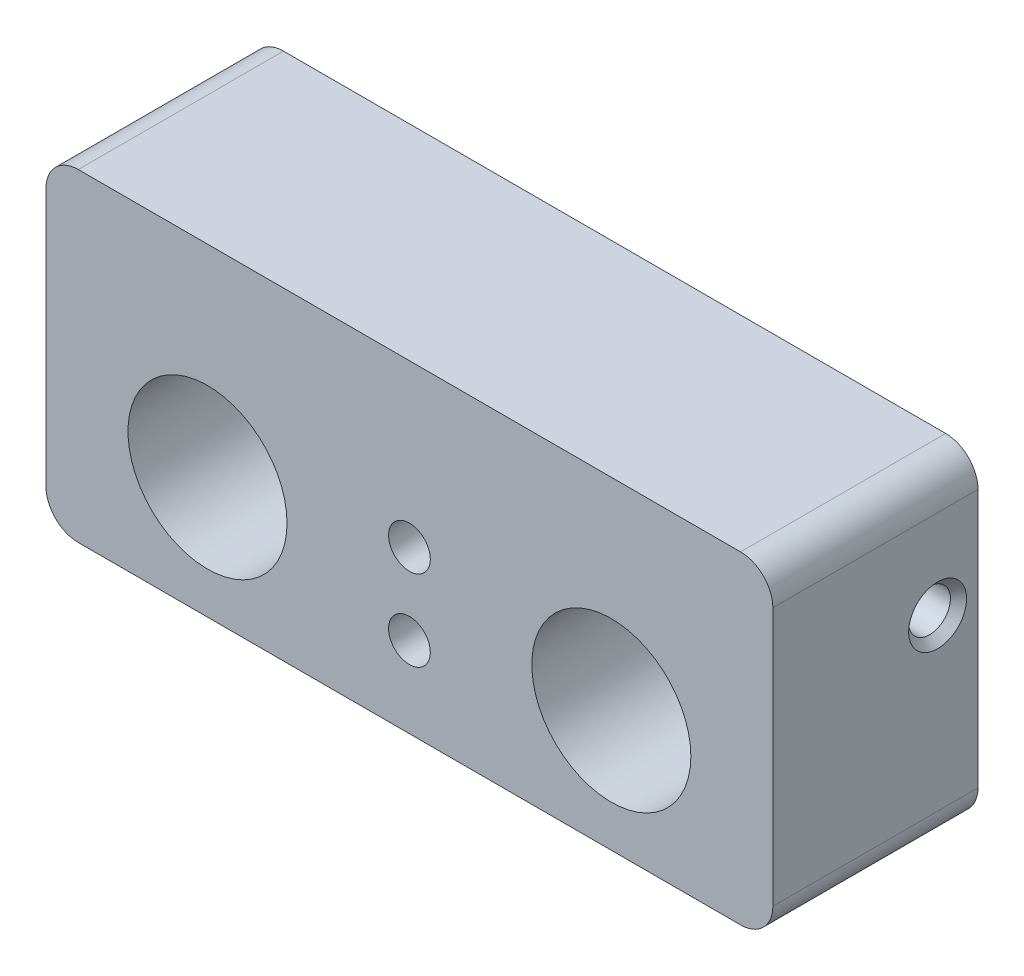
SolidWorks part; units mm, degrees
ref_plane "Front Plane" through (0, 0, 0) normal (0, 0, 1) x (1, 0, 0)
ref_plane "Top Plane" through (0, 0, 0) normal (0, 1, 0) x (1, 0, 0)
ref_plane "Right Plane" through (0, 0, 0) normal (1, 0, 0) x (0, 0, -1)
sketch "Sketch1" plane through (0, 0, 0) normal (0, 0, 1) x (1, 0, 0)
  line L1 (-16.681, 3.7155) -> (28.319, 3.7155)
  line L2 (-16.681, 3.7155) -> (-16.681, -16.2845)
  line L3 (-16.681, -16.2845) -> (28.319, -16.2845)
  line L4 (28.319, 3.7155) -> (28.319, -16.2845)
  circle A0 centre (-6.681, -8.7845) radius 4.9235
  circle A1 centre (18.319, -8.7845) radius 4.9235
  dimension "D3" = 9.847
  dimension "D4" = 9.847
  dimension "D1" = 45
  dimension "D2" = 20
  dimension "D5" = 10
  dimension "D6" = 10
  dimension "D7" = 7.5
  dimension "D8" = 0
  dimension "D9" = 12.5
  dimension "D10" = 25
extrude "Boss-Extrude1" add sketch "Sketch1" along normal blind 12.7
sketch "Sketch2" plane through (0, 0, 12.7) normal (0, 0, 1) x (1, 0, 0)
  line L0 (28.319, -16.2845) -> (28.319, 3.7155) construction
  line L1 (-16.681, 3.7155) -> (28.319, 3.7155)
  line L2 (-16.681, 3.7155) -> (-16.681, -1.2845)
  line L3 (-16.681, -1.2845) -> (28.319, -1.2845)
  line L4 (28.319, 3.7155) -> (28.319, -1.2845)
  line L5 (-16.681, -16.2845) -> (28.319, -16.2845) construction
  circle A0 centre (5.819, -11.2845) radius 1.1148
  circle A1 centre (5.819, -6.2845) radius 0.924
  point P13 (0, 0)
  point P14 (0, 0)
  dimension "D1" = 5
  dimension "D2" = 5
  dimension "D3" = 5
hole_wizard "Tap Drill for M3x0.5 Tap1" positions "Sketch3" profile "Sketch4" hole size "M3x0.5" standard "ANSI Metric"
sketch "Sketch3" plane through (0, 0, 12.7) normal (0, 0, 1) x (1, 0, 0)
  point P0 (5.819, -6.2845)
  point P3 (5.819, -11.2845)
sketch "Sketch4" plane through (5.819, -6.2845, 12.7) normal (1, 0, 0) x (0, -1, 0)
  line L0 (0, 0) -> (0, 10.7765)
  line L1 (0, 10.7765) -> (1.2923, 10)
  line L2 (1.2923, 10) -> (1.2923, 0)
  line L5 (1.2923, 0) -> (0, 0)
  line L10 (0, 10.7765) -> (-1.2923, 10) construction
  line L11 (0, -6.35) -> (0, 107.95) construction
  dimension "Hole Dia." = 2.5846
  dimension "Hole Depth" = 10
  dimension "Drill Angle" = 118
fillet "Fillet1" radius 2 4 edges at (28.319, -16.2845, 6.35) (28.319, 3.7155, 6.35) (-16.681, 3.7155, 6.35) (-16.681, -16.2845, 6.35)
sketch "Sketch5" plane through (-16.681, 0, 0) normal (-1, 0, 0) x (0, 0, 1)
  line L1 (0, 3.7155) -> (12.7, 3.7155) construction
  line L2 (0, 1.7155) -> (0, -14.2845) construction
  circle A0 centre (2.5, -3.7845) radius 1
  dimension "D3" = 2
  dimension "D1" = 7.5
  dimension "D2" = 2.5
hole_wizard "Tap Drill for M3x0.5 Tap2" positions "Sketch6" profile "Sketch8" hole size "M3x0.5" standard "ANSI Metric"
sketch "Sketch6" plane through (-16.681, 0, 0) normal (-1, 0, 0) x (0, 0, 1)
  point P0 (2.5, -3.7845)
sketch "Sketch8" plane through (-16.681, -3.7845, 2.5) normal (0, 1, 0) x (0, 0, 1)
  line L0 (0, 0) -> (0, 5.7765)
  line L1 (0, 5.7765) -> (1.2923, 5)
  line L2 (1.2923, 5) -> (1.2923, 0)
  line L5 (1.2923, 0) -> (0, 0)
  line L10 (0, 5.7765) -> (-1.2923, 5) construction
  line L11 (0, -6.35) -> (0, 107.95) construction
  dimension "Hole Dia." = 2.5846
  dimension "Hole Depth" = 5
  dimension "Drill Angle" = 118
ref_plane "Plane1" through (5.819, 0, 0) normal (1, 0, 0) x (0, 0, -1)
mirror "Mirror3" about plane through (5.819, 0, 0) normal (1, 0, 0) of "Tap Drill for M3x0.5 Tap2"
chamfer "Chamfer1" distance 0.5 angle 45 2 edges at (-16.681, -3.7845, 3.7923) (28.319, -3.7845, 1.2077)
sketch "Sketch10" plane through (0, 0, 12.7) normal (0, 0, 1) x (1, 0, 0)
equation "\"bearing_OD\"=9.847"
equation "\"D3@Sketch1\"=\"bearing_OD\""
equation "\"D4@Sketch1\"=\"bearing_OD\""
equation "\"bearing_width\"=12.7"
equation "\"D1@Boss-Extrude1\"=\"bearing_width\""
